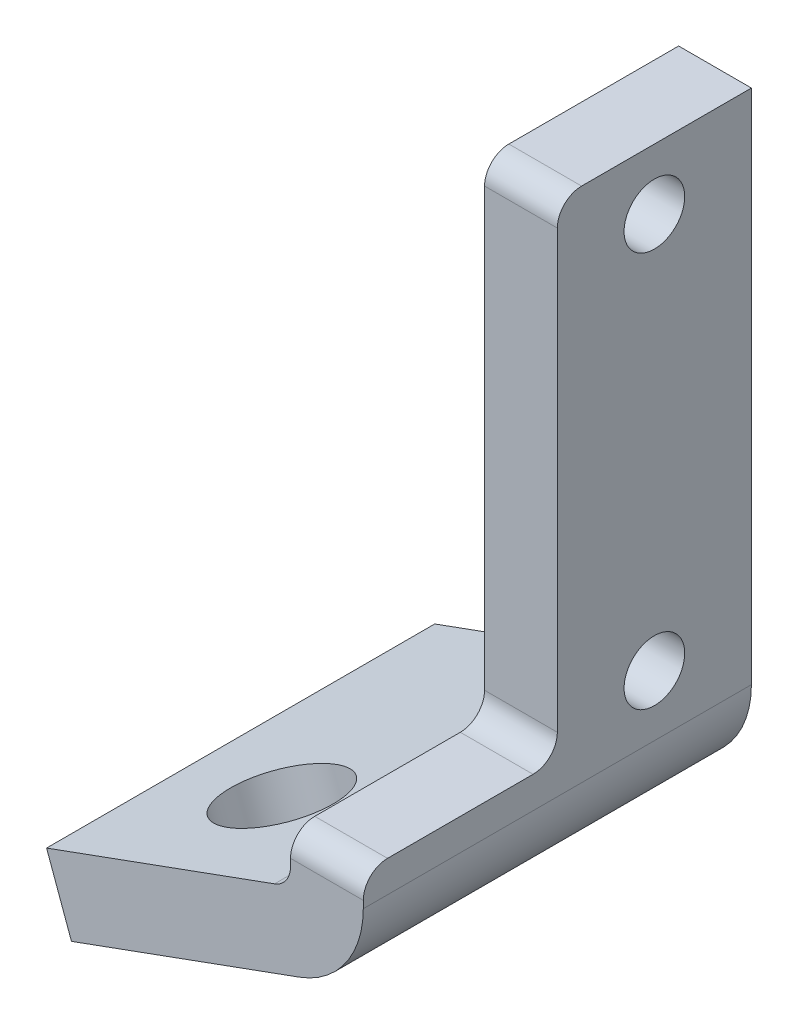
SolidWorks part; units mm, degrees
ref_plane "Front Plane" through (0, 0, 0) normal (0, 0, 1) x (1, 0, 0)
ref_plane "Top Plane" through (0, 0, 0) normal (0, 1, 0) x (1, 0, 0)
ref_plane "Right Plane" through (0, 0, 0) normal (1, 0, 0) x (0, 0, -1)
sketch "Sketch2" plane through (0, 0, 0) normal (0, 0, 1) x (1, 0, 0)
  line L0 (0, 0) -> (0, 16.3) construction
  line L1 (-2.158, -1.9397) -> (-11.5549, -5.3599)
  line L2 (-1.5, 20.3) -> (1.5, 20.3)
  line L3 (-1.5, 20.3) -> (-1.5, -1)
  line L5 (1.5, 20.3) -> (1.5, -1)
  line L6 (-10.5288, -8.179) -> (-1.1319, -4.7588)
  line L7 (-11.5549, -5.3599) -> (-10.5288, -8.179)
  arc A0 (-1.5, -1) -> (-2.158, -1.9397) centre (-2.5, -1) cw
  arc A1 (1.5, -1) -> (-1.1319, -4.7588) centre (-2.5, -1) cw
  point P7 (0, 20.3)
  dimension "D4" = 1
  dimension "D5" = 4
  dimension "D1" = 16.3
  dimension "D2" = 3
  dimension "D3" = 4
  dimension "D6" = 3
  dimension "D7" = 20
  dimension "D8" = 10
  dimension "D9" = 1
extrude "Boss-Extrude2" add sketch "Sketch2" along normal blind 16
sketch "Sketch6" plane through (-1.5, 0, 0) normal (-1, 0, 0) x (0, 0, 1)
  line L0 (0, 20.3) -> (0, -1) construction
  line L1 (16, 20.3) -> (0, 20.3) construction
  line L2 (8, 20.3) -> (8, 0.3)
  line L3 (8, 0.3) -> (16, 0.3)
  line L4 (16, 20.3) -> (16, -1) construction
  line L5 (8, 20.3) -> (16, 20.3)
  line L6 (16, 20.3) -> (16, 0.3)
  circle A0 centre (4, 17.8) radius 1.25
  circle A1 centre (4, 1.5) radius 1.25
  dimension "D4" = 2.5
  dimension "D1" = 16.3
  dimension "D2" = 4
  dimension "D3" = 2.5
  dimension "D5" = 4
  dimension "D6" = 20
sketch "Sketch7" plane through (0.371, -1.0192, 0) normal (-0.342, 0.9397, 0) x (0.9397, 0.342, 0)
  line L0 (-2.6913, 0) -> (-12.6913, 0) construction
  line L2 (-2.6913, -16) -> (-12.6913, -16) construction
  circle A0 centre (-7.6913, -11) radius 2.25
  point P2 (0, 0)
  point P5 (-7.6913, 0)
  dimension "D1" = 4.5
  dimension "D2" = 5
extrude "Cut-Extrude4" cut sketch "Sketch7" against normal through all
extrude "Cut-Extrude5" cut sketch "Sketch6" against normal through all
fillet "Fillet2" radius 1 3 edges at (0, 0.3, 16) (0, 0.3, 8) (0, 20.3, 8)
